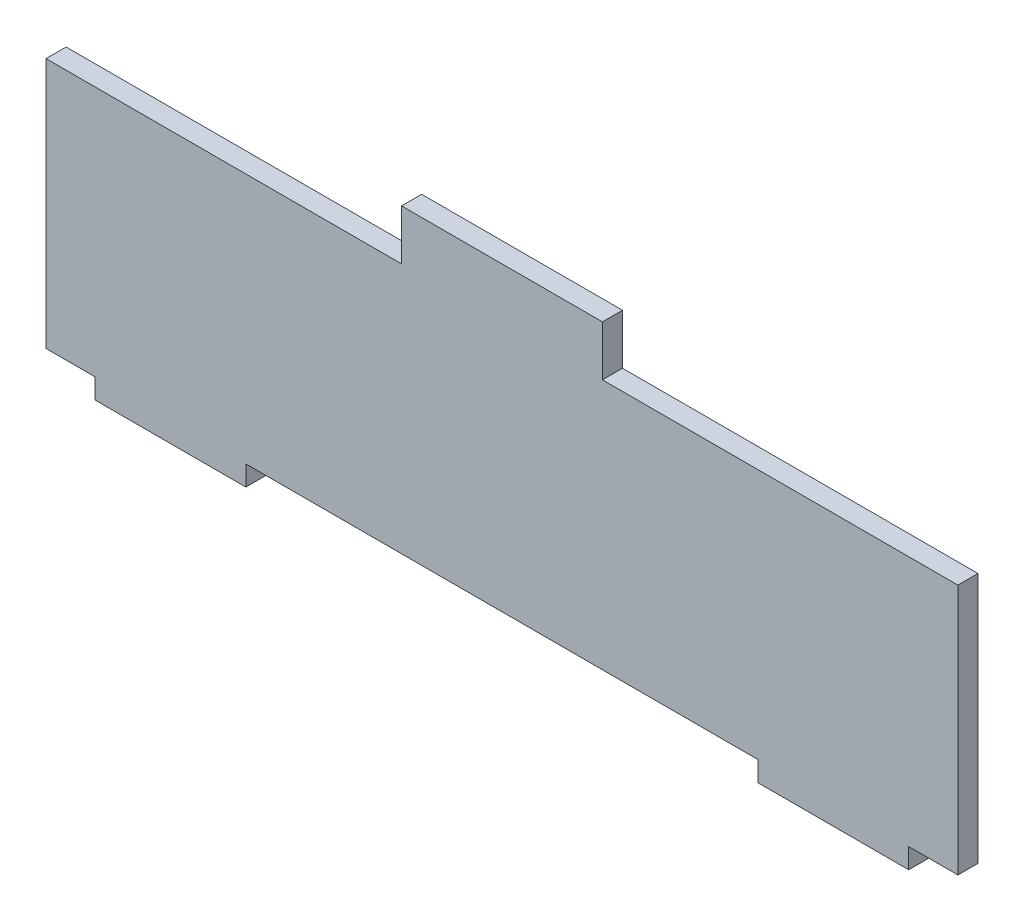
SolidWorks part; units mm, degrees
material "Aleación 6061"
ref_plane "Alzado" through (0, 0, 0) normal (0, 0, 1) x (1, 0, 0)
ref_plane "Planta" through (0, 0, 0) normal (0, 1, 0) x (1, 0, 0)
ref_plane "Vista lateral" through (0, 0, 0) normal (1, 0, 0) x (0, 0, -1)
sketch "Croquis1" plane through (0, 0, 0) normal (0, 0, 1) x (1, 0, 0)
  line L0 (-81, -25) -> (-81, -29)
  line L1 (-90.8, -25) -> (-81, -25)
  line L2 (-90.8, -25) -> (-90.8, 25)
  line L3 (-90.8, 25) -> (-20, 25)
  line L4 (90.8, -25) -> (90.8, 25)
  line L5 (-90.8, -25) -> (90.8, 25) construction
  line L6 (-90.8, 25) -> (90.8, -25) construction
  line L7 (-81, -29) -> (-51, -29)
  line L8 (-51, -29) -> (-51, -25)
  line L9 (-20, 25) -> (-20, 35)
  line L10 (-20, 35) -> (20, 35)
  line L11 (20, 35) -> (20, 25)
  line L12 (51, -25) -> (51, -29)
  line L13 (51, -29) -> (81, -29)
  line L14 (81, -29) -> (81, -25)
  line L15 (-51, -25) -> (51, -25)
  line L16 (20, 25) -> (90.8, 25)
  line L17 (81, -25) -> (90.8, -25)
  point P0 (0, 0)
  point P19 (0, 35)
  dimension "D1" = 50
  dimension "D2" = 181.6
  dimension "D3" = 9.8
  dimension "D4" = 9.8
  dimension "D5" = 4
  dimension "D6" = 30
  dimension "D7" = 40
  dimension "D8" = 10
extrude "Saliente-Extruir1" add sketch "Croquis1" along normal blind 4
